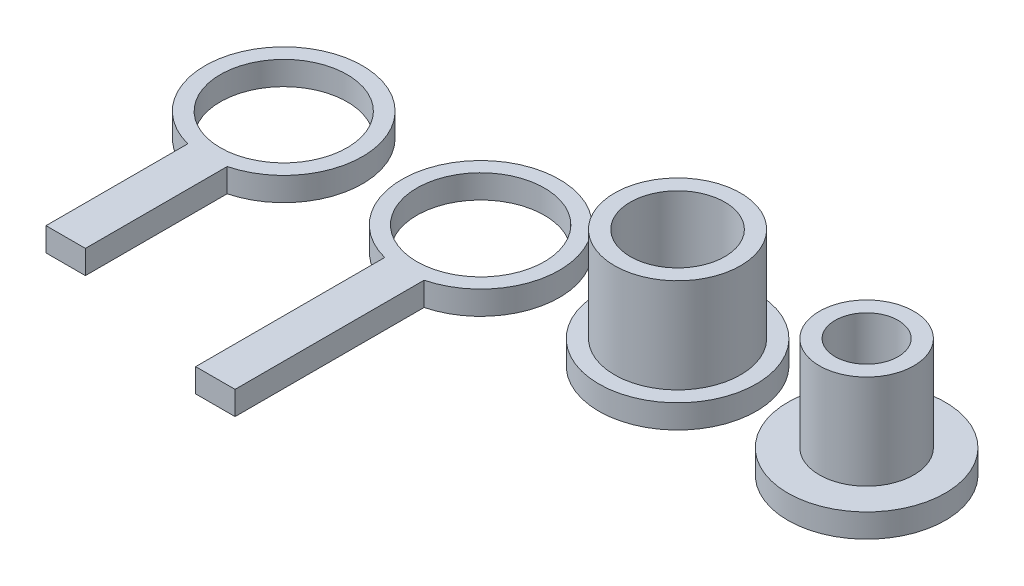
SolidWorks part; units mm, degrees
ref_plane "Спереди" through (0, 0, 0) normal (0, 0, 1) x (1, 0, 0)
ref_plane "Сверху" through (0, 0, 0) normal (0, 1, 0) x (1, 0, 0)
ref_plane "Справа" through (0, 0, 0) normal (1, 0, 0) x (0, 0, -1)
other "Configuration Table"
sketch "Эскиз1" plane through (0, 0, 0) normal (0, 1, 0) x (1, 0, 0)
  line L1 (0, 0) -> (24, 0) construction
  circle A0 centre (0, 0) radius 10
  circle A1 centre (24, 0) radius 10
  dimension "D1" = 20
  dimension "D2" = 20
  dimension "D3" = 24
extrude "Бобышка-Вытянуть1" add sketch "Эскиз1" along normal blind 3
sketch "Эскиз3" plane through (0, 3, 0) normal (0, 1, 0) x (1, 0, 0)
  circle A0 centre (0, 0) radius 8
  dimension "D1" = 16
sketch "Эскиз4" plane through (0, 3, 0) normal (0, 1, 0) x (1, 0, 0)
  circle A0 centre (24, 0) radius 6
  dimension "D1" = 12
extrude "Бобышка-Вытянуть2" add sketch "Эскиз4" along normal blind 12
extrude "Бобышка-Вытянуть3" add sketch "Эскиз3" along normal blind 12
sketch "Эскиз5" plane through (0, 0, 0) normal (0, 1, 0) x (1, 0, 0)
  line L0 (0, 0) -> (-25, 0) construction
  line L1 (-25, 0) -> (-50, 0) construction
  line L6 (-50, -8.05) -> (-50, -17.8662) construction
  line L7 (-25, -8.1) -> (-25, -20.8912) construction
  line L21 (-52.5, -27.6825) -> (-47.5, -27.6825)
  line L22 (-52.5, -27.6825) -> (-52.5, -9.6825)
  line L24 (-47.5, -27.6825) -> (-47.5, -9.6825)
  line L25 (-52.5, -27.6825) -> (-47.5, -8.05) construction
  line L26 (-52.5, -8.05) -> (-47.5, -27.6825) construction
  line L27 (-27.5, -33.6825) -> (-22.5, -33.6825)
  line L28 (-27.5, -33.6825) -> (-27.5, -9.6825)
  line L30 (-22.5, -33.6825) -> (-22.5, -9.6825)
  line L31 (-27.5, -33.6825) -> (-22.5, -8.1) construction
  line L32 (-27.5, -8.1) -> (-22.5, -33.6825) construction
  line L42 (-52.5, -9.6825) -> (-52.5, -8.05) construction
  line L43 (-52.5, -8.05) -> (-50, -8.05) construction
  line L44 (-50, -8.05) -> (-47.5, -8.05) construction
  line L45 (-47.5, -8.05) -> (-47.5, -9.6825) construction
  line L46 (-52.5, -9.6825) -> (-47.5, -9.6825) construction
  line L47 (-27.5, -9.6825) -> (-22.5, -9.6825) construction
  line L48 (-22.5, -8.1) -> (-25, -8.1) construction
  line L49 (-25, -8.1) -> (-27.5, -8.1) construction
  line L50 (-27.5, -8.1) -> (-27.5, -9.6825) construction
  line L51 (-22.5, -9.6825) -> (-22.5, -8.1) construction
  circle A0 centre (-25, 0) radius 8.1
  arc A1 (-22.5, -9.6825) -> (-27.5, -9.6825) centre (-25, 0) ccw
  circle A2 centre (-50, 0) radius 8.05
  arc A3 (-47.5, -9.6825) -> (-52.5, -9.6825) centre (-50, 0) ccw
  dimension "D5" = 25
  dimension "D6" = 25
  dimension "D7" = 16.1
  dimension "D8" = 16.2
  dimension "D9" = 18
  dimension "D10" = 24
  dimension "D3" = 10
  dimension "D4" = 10
  dimension "D19" = 5
  dimension "D20" = 5
extrude "Бобышка-Вытянуть4" add sketch "Эскиз5" along normal blind 3 separate body
sketch "Эскиз10" plane through (0, 15, 0) normal (0, 1, 0) x (1, 0, 0)
  circle A0 centre (0, 0) radius 6
  dimension "D1" = 12
extrude "Вырез-Вытянуть1" cut sketch "Эскиз10" against normal through all
sketch "Эскиз11" plane through (0, 15, 0) normal (0, 1, 0) x (1, 0, 0)
  circle A0 centre (24, 0) radius 4
  dimension "D1" = 8
extrude "Вырез-Вытянуть2" cut sketch "Эскиз11" against normal through all
